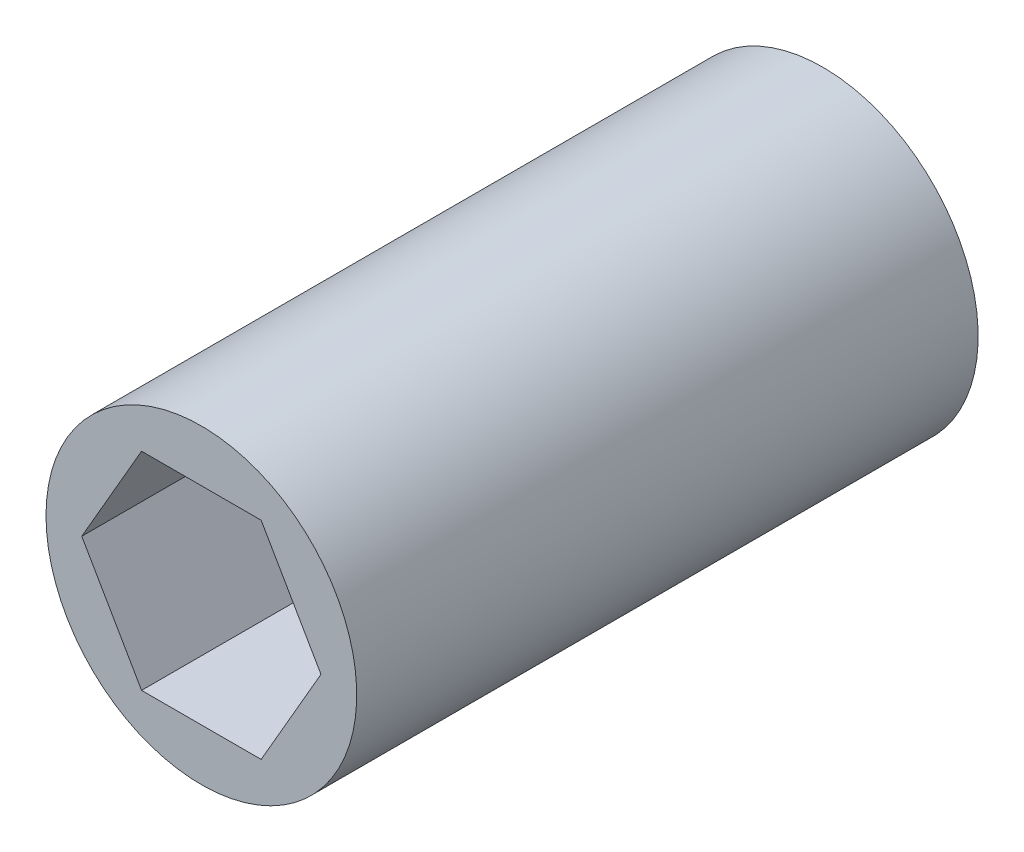
SolidWorks part; units mm, degrees
ref_plane "Front Plane" through (0, 0, 0) normal (0, 0, 1) x (1, 0, 0)
ref_plane "Top Plane" through (0, 0, 0) normal (0, 1, 0) x (1, 0, 0)
ref_plane "Right Plane" through (0, 0, 0) normal (1, 0, 0) x (0, 0, -1)
sketch "Sketch1" plane through (0, 0, 0) normal (0, 0, 1) x (1, 0, 0)
  line L1 (-7.3323, 0) -> (-3.6662, -6.35)
  line L2 (-3.6662, -6.35) -> (3.6662, -6.35)
  line L3 (3.6662, -6.35) -> (7.3323, 0)
  line L4 (7.3323, 0) -> (3.6662, 6.35)
  line L5 (3.6662, 6.35) -> (-3.6662, 6.35)
  line L6 (-3.6662, 6.35) -> (-7.3323, 0)
  circle A0 centre (0, 0) radius 9.525
  circle A1 centre (0, 0) radius 6.35 construction
  dimension "D1" = 12.7
  dimension "D2" = 19.05
extrude "Boss-Extrude1" add sketch "Sketch1" along normal blind 38.1
